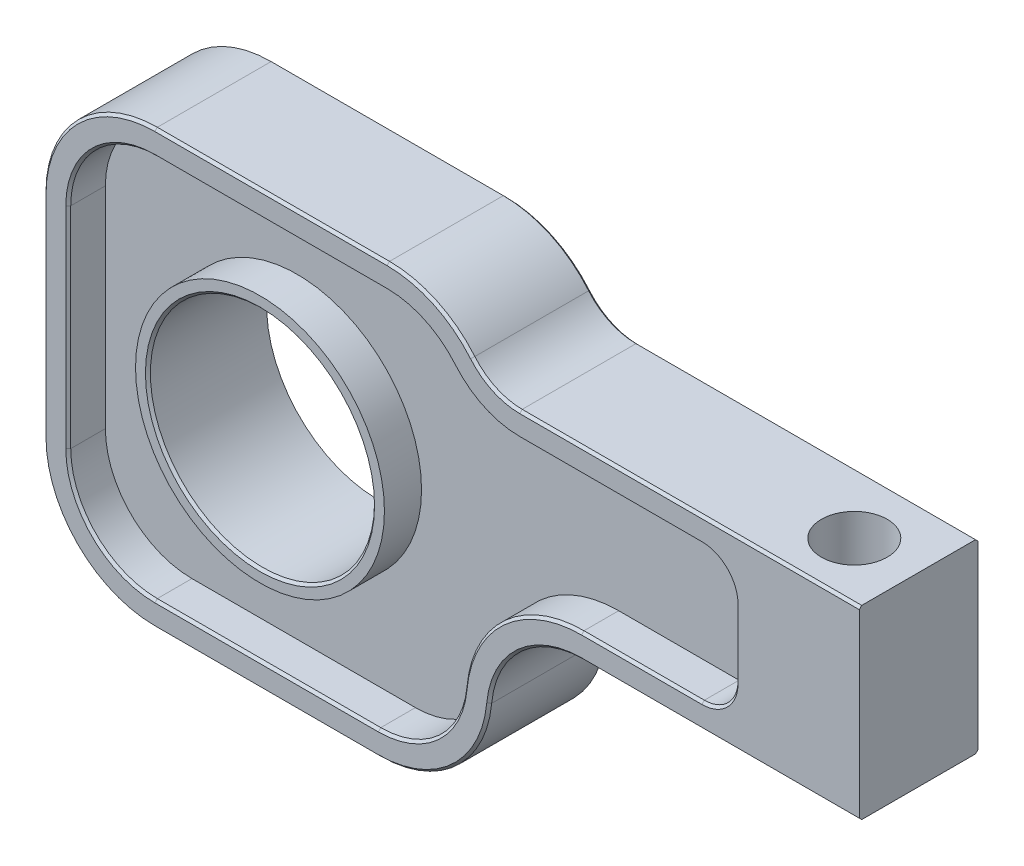
SolidWorks part; units mm, degrees
material "6061 Alloy"
ref_plane "Front Plane" through (0, 0, 0) normal (0, 0, 1) x (1, 0, 0)
ref_plane "Top Plane" through (0, 0, 0) normal (0, 1, 0) x (1, 0, 0)
ref_plane "Right Plane" through (0, 0, 0) normal (1, 0, 0) x (0, 0, -1)
sketch "Sketch1" plane through (0, 0, 0) normal (0, 0, 1) x (1, 0, 0)
  line L1 (0, 0) -> (96.52, 0)
  line L2 (0, 0) -> (0, -44.45)
  line L3 (0, -44.45) -> (96.52, -44.45)
  line L4 (96.52, 0) -> (96.52, -44.45)
  dimension "D1" = 44.45
  dimension "D2" = 96.52
extrude "Boss-Extrude1" add sketch "Sketch1" along normal mid plane 12.192
sketch "Sketch2" plane through (0, 0, 6.096) normal (0, 0, 1) x (1, 0, 0)
  circle A0 centre (22.225, -22.225) radius 11.5087
  dimension "D1" = 23.0175
  dimension "D2" = 22.225
  dimension "D3" = 22.225
extrude "Cut-Extrude1" cut sketch "Sketch2" against normal up to next
sketch "Sketch3" plane through (0, 0, 0) normal (0, 1, 0) x (1, 0, 0)
  line L1 (96.52, 6.096) -> (0, 6.096) construction
  line L2 (96.52, -6.096) -> (96.52, 6.096) construction
  circle A0 centre (77.4065, -0.254) radius 3.3782
  dimension "D1" = 6.7564
  dimension "D2" = 19.1135
  dimension "D3" = 6.35
extrude "Cut-Extrude2" cut sketch "Sketch3" against normal up to next
sketch "Sketch4" plane through (0, 0, 6.096) normal (0, 0, 1) x (1, 0, 0)
  line L0 (48.895, 0) -> (96.52, 0) construction
  line L1 (96.52, 0) -> (0, 0) construction
  line L2 (48.895, 6.35) -> (96.52, 6.35)
  line L3 (48.895, -6.35) -> (96.52, -6.35)
  line L4 (96.52, -34.925) -> (55.245, -34.925) construction
  line L5 (45.72, -34.925) -> (45.72, -44.45)
  line L8 (96.52, -44.45) -> (96.52, 0) construction
  line L9 (96.52, -44.45) -> (55.245, -44.45)
  line L10 (96.52, -25.4) -> (55.245, -25.4)
  line L11 (0, -44.45) -> (96.52, -44.45) construction
  line L12 (45.72, -44.45) -> (55.245, -44.45)
  arc A0 (48.895, 6.35) -> (48.895, -6.35) centre (48.895, 0) ccw
  arc A1 (96.52, -6.35) -> (96.52, 6.35) centre (96.52, 0) ccw
  arc A4 (96.52, -44.45) -> (96.52, -25.4) centre (96.52, -34.925) ccw
  arc A5 (55.245, -25.4) -> (45.72, -34.925) centre (55.245, -34.925) ccw
  point P5 (72.7075, 0)
  dimension "D1" = 6.35
  dimension "D3" = 9.525
  dimension "D2" = 47.625
  dimension "D4" = 41.275
extrude "Cut-Extrude3" cut sketch "Sketch4" against normal up to next
sketch "Sketch7" plane through (0, -6.35, 0) normal (0, 1, 0) x (1, 0, 0)
  line L0 (96.52, 6.096) -> (48.895, 6.096) construction
  line L1 (96.52, -6.096) -> (83.7565, -6.096)
  line L2 (96.52, -6.096) -> (96.52, 6.096)
  line L3 (96.52, 6.096) -> (83.7565, 6.096)
  line L4 (83.7565, -6.096) -> (83.7565, 6.096)
  dimension "D1" = 12.7635
extrude "Cut-Extrude5" cut sketch "Sketch7" against normal through all
fillet "Fillet1" radius 11.43 4 edges at (42.545, 0, 0) (45.72, -44.45, 0) (0, -44.45, 0) (0, 0, 0)
sketch "Sketch5" plane through (0, 0, 6.096) normal (0, 0, 1) x (1, 0, 0)
  line L47 (71.0565, -12.3444) -> (71.0565, -19.4056)
  line L48 (83.7565, -25.4) -> (83.7565, -6.35) construction
  line L53 (81.2165, -22.86) -> (81.2165, -8.89)
  line L54 (55.245, -22.86) -> (81.2165, -22.86)
  line L55 (11.43, -41.91) -> (34.3768, -41.91)
  line L56 (2.54, -11.43) -> (2.54, -33.02)
  line L57 (35.2758, -2.54) -> (11.43, -2.54)
  line L58 (81.2165, -8.89) -> (48.895, -8.89)
  line L60 (55.245, -22.86) -> (67.6021, -22.86)
  line L61 (11.43, -41.91) -> (34.3768, -41.91)
  line L62 (2.54, -11.43) -> (2.54, -33.02)
  line L63 (35.2758, -2.54) -> (11.43, -2.54)
  line L64 (67.6021, -8.89) -> (48.895, -8.89)
  arc A53 (67.6021, -22.86) -> (71.0565, -19.4056) centre (67.6021, -19.4056) ccw
  circle A54 centre (22.225, -22.225) radius 12.7787
  circle A55 centre (22.225, -22.225) radius 12.7787
  arc A56 (71.0565, -12.3444) -> (67.6021, -8.89) centre (67.6021, -12.3444) ccw
  arc A58 (55.245, -22.86) -> (43.23, -33.8282) centre (55.245, -34.925) ccw
  arc A59 (34.3768, -41.91) -> (43.23, -33.8282) centre (34.3768, -33.02) ccw
  arc A60 (2.54, -33.02) -> (11.43, -41.91) centre (11.43, -33.02) ccw
  arc A61 (11.43, -2.54) -> (2.54, -11.43) centre (11.43, -11.43) ccw
  arc A62 (42.0854, -5.715) -> (48.895, -8.89) centre (48.895, 0) ccw
  arc A63 (42.0854, -5.715) -> (35.2758, -2.54) centre (35.2758, -11.43) ccw
  arc A64 (55.245, -22.86) -> (43.23, -33.8282) centre (55.245, -34.925) ccw
  arc A65 (34.3768, -41.91) -> (43.23, -33.8282) centre (34.3768, -33.02) ccw
  arc A66 (2.54, -33.02) -> (11.43, -41.91) centre (11.43, -33.02) ccw
  arc A67 (11.43, -2.54) -> (2.54, -11.43) centre (11.43, -11.43) ccw
  arc A68 (42.0854, -5.715) -> (48.895, -8.89) centre (48.895, 0) ccw
  arc A69 (42.0854, -5.715) -> (35.2758, -2.54) centre (35.2758, -11.43) ccw
  dimension "D4" = 3.4544
  dimension "D3" = 12.7
  dimension "D1" = 2.54
  dimension "D2" = 1.27
extrude "Cut-Extrude4" cut sketch "Sketch5" against normal blind 3.81
mirror "Mirror3" about plane through (0, 0, 0) normal (0, 0, 1) of "Cut-Extrude4"
chamfer "Chamfer1" distance 0.254 angle 45 51 edges at (33.7337, -22.225, 6.096) (70.0447, -21.8482, 6.096) (70.0447, -9.9018, 6.096) (0, -22.225, 6.096) (3.3478, -41.1022, 6.096) (22.9034, -44.45, 6.096) (42.0829, -41.4616, 6.096) (48.8232, -27.8903, 6.096) (69.5007, -25.4, 6.096) (66.3257, -6.35, 6.096) (46.2116, -5.7552, 6.096) (40.1058, -1.0707, 6.096) (23.3529, 0, 6.096) (3.3478, -3.3478, 6.096) (70.0447, -9.9018, -6.096) (70.0447, -21.8482, -6.096) (69.5007, -25.4, -6.096) (48.8232, -27.8903, -6.096) (42.0829, -41.4616, -6.096) (22.9034, -44.45, -6.096) (3.3478, -41.1022, -6.096) (0, -22.225, -6.096) (3.3478, -3.3478, -6.096) (23.3529, 0, -6.096) (40.1058, -1.0707, -6.096) (46.2116, -5.7552, -6.096) (66.3257, -6.35, -6.096) (5.1438, -5.1438, -6.096) (2.54, -22.225, -6.096) (23.3529, -2.54, -6.096) (5.1438, -39.3062, -6.096) (39.0325, -3.3728, -6.096) (22.9034, -41.91, -6.096) (45.1383, -8.0572, -6.096) (40.3704, -39.5857, -6.096) (58.2485, -8.89, -6.096) (47.1108, -26.0144, -6.096) (61.4235, -22.86, -6.096) (71.0565, -15.875, -6.096) (5.1438, -39.3062, 6.096) (22.9034, -41.91, 6.096) (2.54, -22.225, 6.096) (40.3704, -39.5857, 6.096) (5.1438, -5.1438, 6.096) (47.1108, -26.0144, 6.096) (23.3529, -2.54, 6.096) (61.4235, -22.86, 6.096) (39.0325, -3.3728, 6.096) (45.1383, -8.0572, 6.096) (71.0565, -15.875, 6.096) (58.2485, -8.89, 6.096)
sketch "Sketch6" plane through (0, 0, 2.286) normal (0, 0, 1) x (1, 0, 0)
  line L0 (22.225, -22.225) -> (22.225, 49977.775) construction
  line L1 (35.2758, -2.54) -> (11.43, -2.54) construction
  circle A0 centre (22.225, -5.9652) radius 3.4252
  circle A1 centre (22.225, -22.225) radius 12.8346 construction
